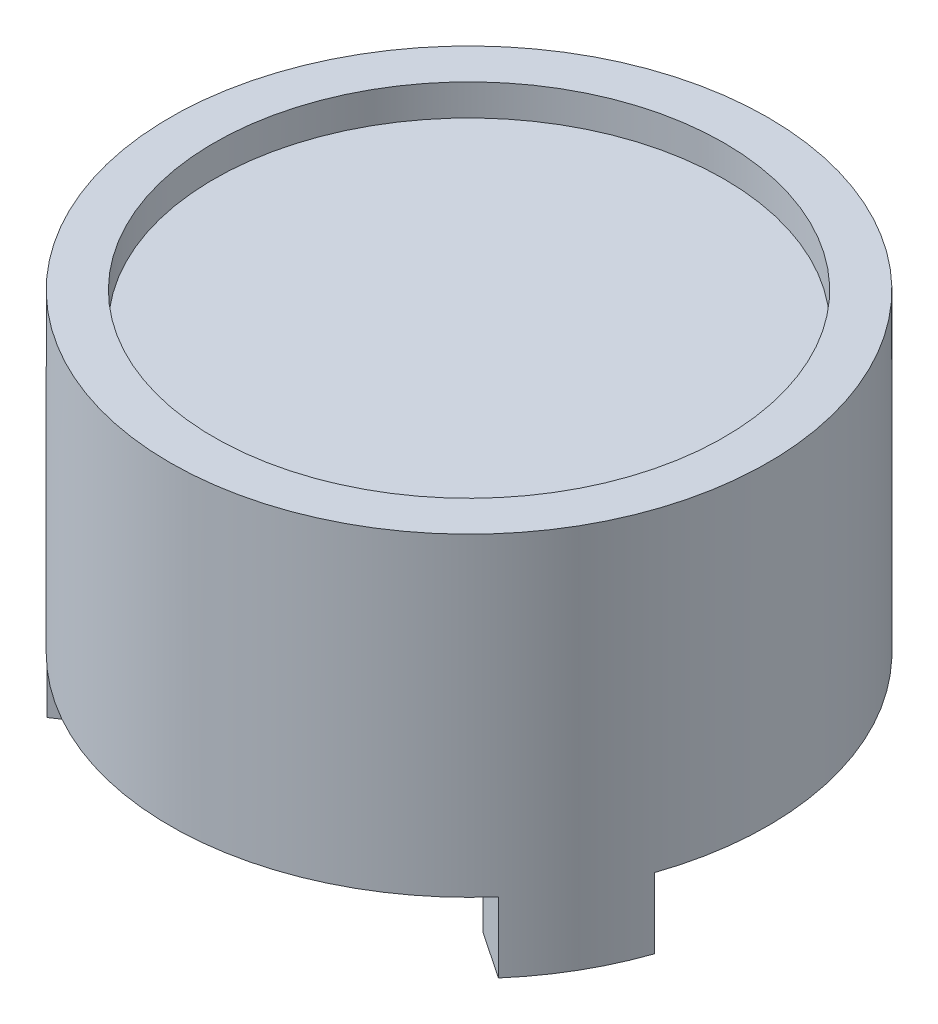
SolidWorks part; units mm, degrees
ref_plane "Front" through (0, 0, 0) normal (0, 0, 1) x (1, 0, 0)
ref_plane "Top" through (0, 0, 0) normal (0, 1, 0) x (1, 0, 0)
ref_plane "Right" through (0, 0, 0) normal (1, 0, 0) x (0, 0, -1)
sketch "Sketch4" plane through (0, 0, 0) normal (0, 0, 1) x (1, 0, 0)
  line L0 (0, 0) -> (0, 16.1036) construction
  line L1 (0, 16.1036) -> (14.5, 16.1036)
  line L2 (13.5, 1) -> (13.5, 0)
  line L3 (13.5, 0) -> (17, 0)
  line L4 (17, 0) -> (17, 17.8816)
  line L5 (17, 17.8816) -> (14.5, 17.8816)
  line L6 (14.5, 17.8816) -> (14.5, 16.1036)
  line L7 (14.5, 1) -> (13.5, 1)
  line L8 (14.5, 3.4036) -> (0, 3.4036)
  line L9 (0, 3.4036) -> (0, 16.1036)
  line L10 (14.5, 3.4036) -> (14.5, 1)
  dimension "D1" = 34
  dimension "D2" = 2.5
  dimension "D3" = 27
  dimension "D4" = 1
  dimension "D5" = 17.8816
  dimension "D6" = 12.7
  dimension "D7" = 1.778
revolve "Revolve1" add sketch "Sketch4" angle 360 about L0
sketch "Sketch3" plane through (0, 0, 0) normal (0, 1, 0) x (1, 0, 0)
  line L0 (-3.25, 16.6864) -> (-3, 13.1624)
  line L1 (3.25, 16.6864) -> (3, 13.1624)
  line L2 (0, 0) -> (0, 17) construction
  arc A0 (-3.25, 16.6864) -> (3.25, 16.6864) centre (0, 0) cw
  arc A3 (3, 13.1624) -> (-3, 13.1624) centre (0, 0) ccw
  circle A4 centre (0, 0) radius 13.5 construction
  circle A6 centre (0, 0) radius 17 construction
  circle A8 centre (0, 0) radius 13.5 construction
  dimension "D1" = 6
  dimension "D2" = 6.5
extrude "Tooth" add sketch "Sketch3" against normal blind 4
pattern_circular "Three Teeth" count 3 over 360 about axis through (0, 0, 0) along (0, 1, 0) of "Tooth"
fillet "Fillet1" radius 0.254 6 edges
